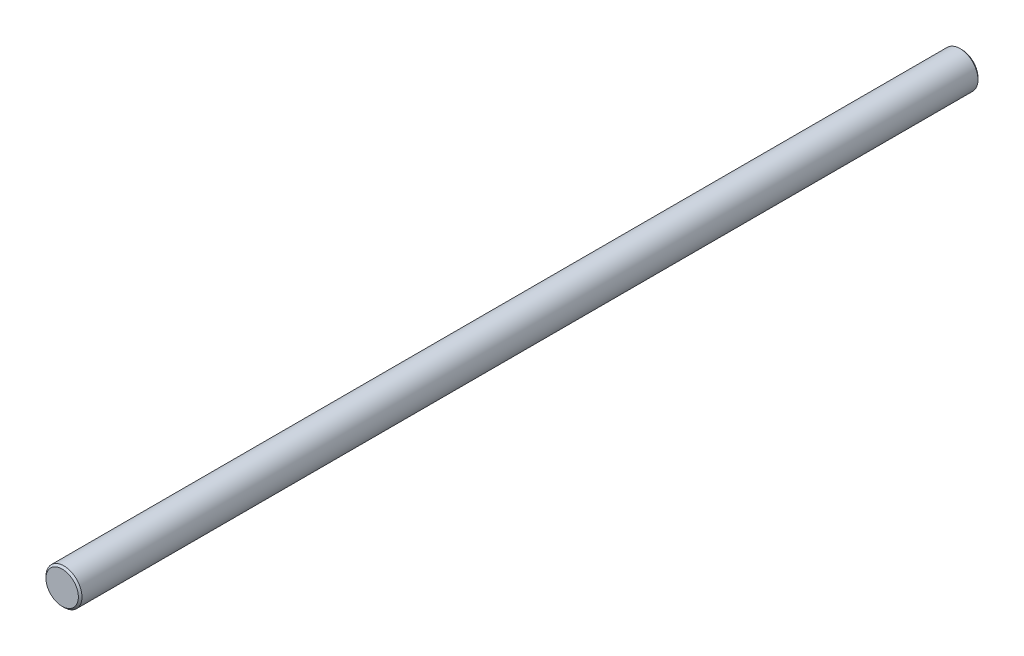
SolidWorks part; units mm, degrees
ref_plane "Front" through (0, 0, 0) normal (0, 0, 1) x (1, 0, 0)
ref_plane "Top" through (0, 0, 0) normal (0, 1, 0) x (1, 0, 0)
ref_plane "Right" through (0, 0, 0) normal (1, 0, 0) x (0, 0, -1)
sketch "Esquisse1" plane through (0, 0, 0) normal (0, 0, 1) x (1, 0, 0)
  circle A0 centre (0, 0) radius 10
  dimension "D1" = 20
extrude "Boss.-Extru.1" add sketch "Esquisse1" along normal blind 500
chamfer "Chanfrein1" distance 1 angle 45 2 edges at (10, 0, 500) (10, 0, 0)
